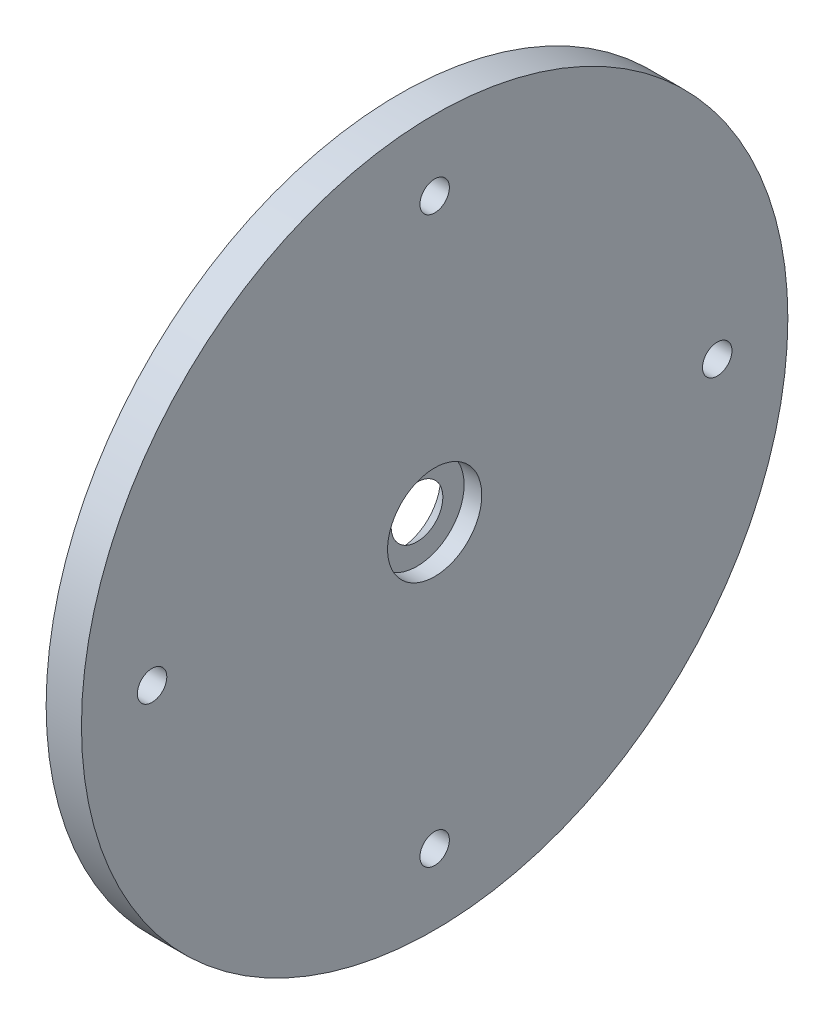
SolidWorks part; units mm, degrees
material "AISI 304"
ref_plane "Front" through (0, 0, 0) normal (0, 0, 1) x (1, 0, 0)
ref_plane "Top" through (0, 0, 0) normal (0, 1, 0) x (1, 0, 0)
ref_plane "Right" through (0, 0, 0) normal (1, 0, 0) x (0, 0, -1)
sketch "Sketch1" plane through (0, 0, 0) normal (1, 0, 0) x (0, 0, -1)
  circle A0 centre (0, 0) radius 95.25
  dimension "D1" = 190.5
extrude "Boss-Extrude1" add sketch "Sketch1" along normal blind 9.525
sketch "Sketch2" plane through (9.525, 0, 0) normal (1, 0, 0) x (0, 0, -1)
  circle A0 centre (0, 0) radius 12.7
  dimension "D1" = 25.4
extrude "Cut-Extrude1" cut sketch "Sketch2" against normal blind 4.7625
hole_wizard "CSK for 1/2 Flat Head Machine Screw1" positions "Sketch3" profile "Sketch4" countersink size "1/2" standard "ANSI Inch"
sketch "Sketch3" plane through (0, 0, 0) normal (-1, 0, 0) x (0, 0, 1)
  point P0 (0, 0)
sketch "Sketch4" plane through (0, 0, 0) normal (0, 1, 0) x (0, 0, 1)
  line L0 (0, 0) -> (0, 9.525)
  line L1 (0, 9.525) -> (6.7462, 9.525)
  line L2 (6.7462, 9.525) -> (6.7462, 5.0228)
  line L3 (6.7462, 5.0228) -> (11.1125, 0)
  line L5 (11.1125, 0) -> (0, 0)
  line L6 (-6.7462, 5.0228) -> (-11.1125, 0) construction
  line L11 (0, -6.35) -> (0, 107.95) construction
  dimension "Thru Hole Dia." = 13.4925
  dimension "Thru Hole Depth" = 9.525
  dimension "Near C'Sink Dia." = 22.225
  dimension "Near C'Sink Angle" = 82
hole_wizard "3/8-16 Tapped Hole1" positions "Sketch5" profile "Sketch6" tap size "3/8-16" standard "ANSI Inch"
sketch "Sketch5" plane through (9.525, 0, 0) normal (1, 0, 0) x (0, 0, -1)
  circle A0 centre (0, 0) radius 12.7 construction
  circle A1 centre (0, 0) radius 6.9725 construction
  point P0 (0, -76.2)
  dimension "D1" = 0
  dimension "D2" = 76.2
cosmetic thread "Hole Thread1"
sketch "Sketch6" plane through (9.525, -76.2, 0) normal (0, 1, 0) x (0, 0, -1)
  line L0 (0, 0) -> (0, 9.525)
  line L1 (0, 9.525) -> (3.9687, 9.525)
  line L2 (3.9687, 9.525) -> (3.9687, 0)
  line L5 (3.9687, 0) -> (0, 0)
  line L11 (0, -6.35) -> (0, 107.95) construction
  dimension "Thru Tap Drill Dia." = 7.9375
  dimension "Thru Tap Drill Depth" = 9.525
pattern_circular "CirPattern1" count 4 over 360 about axis through (0, 0, 0) along (1, 0, 0) of "3/8-16 Tapped Hole1"
cosmetic thread "Hole Thread2"
cosmetic thread "Hole Thread3"
cosmetic thread "Hole Thread4"
